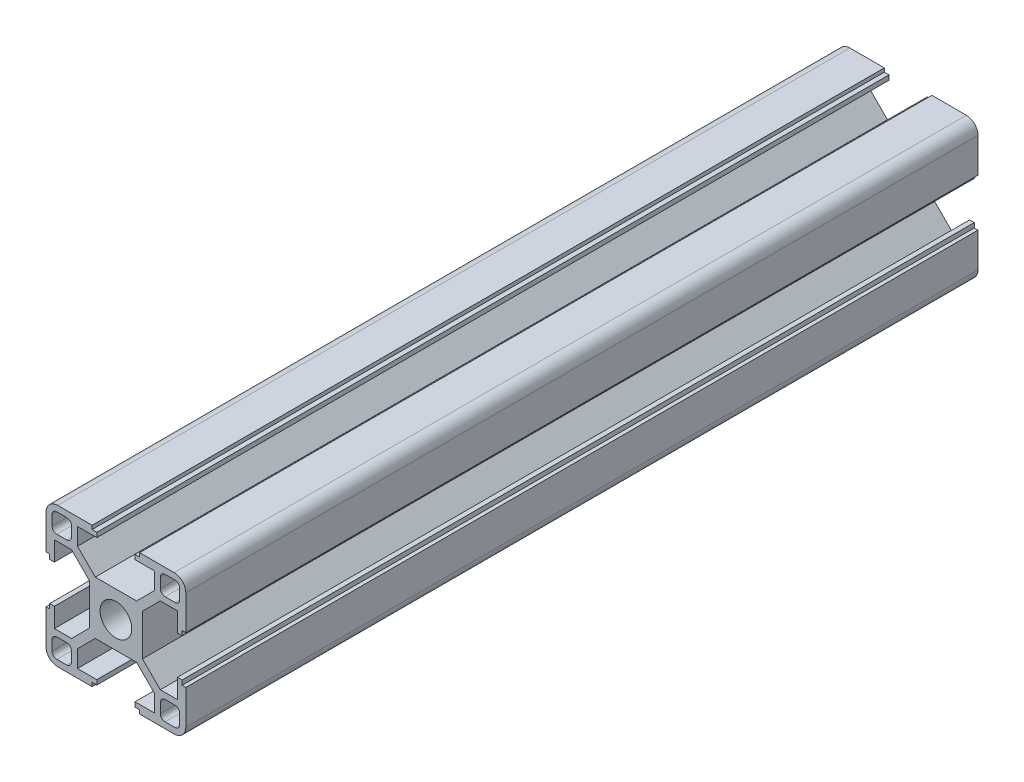
SolidWorks part; units mm, degrees
material "6061-T6 (SS)"
ref_plane "前视基准面" through (0, 0, 0) normal (0, 0, 1) x (1, 0, 0)
ref_plane "上视基准面" through (0, 0, 0) normal (0, 1, 0) x (1, 0, 0)
ref_plane "右视基准面" through (0, 0, 0) normal (1, 0, 0) x (0, 0, -1)
sketch "Sketch1" plane through (0, 0, 0) normal (0, 0, 1) x (1, 0, 0)
  line L0 (-5.1, 15) -> (-5.1, 14.2)
  line L1 (-12.5, -15) -> (12.5, -15)
  line L2 (-15, -12.5) -> (-15, 12.5)
  line L3 (-12.5, 15) -> (12.5, 15)
  line L4 (15, -12.5) -> (15, 12.5)
  line L5 (-15, -15) -> (15, 15) construction
  line L6 (-15, 15) -> (15, -15) construction
  line L7 (-5.1, 14.2) -> (-4.1, 14.2)
  line L8 (-4.1, 14.2) -> (-4.1, 13.2)
  line L9 (-4.1, 13.2) -> (-8.25, 13.2)
  line L10 (-8.25, 13.2) -> (-8.25, 9.5228)
  line L11 (-8.25, 9.5228) -> (-4.4272, 5.7)
  line L12 (-4.4272, 5.7) -> (4.4272, 5.7)
  line L13 (-5.1, 15) -> (5.1, 15)
  line L14 (0, 15) -> (0, 5.7) construction
  line L15 (8.25, 9.5228) -> (4.4272, 5.7)
  line L16 (8.25, 13.2) -> (8.25, 9.5228)
  line L17 (4.1, 13.2) -> (8.25, 13.2)
  line L18 (4.1, 14.2) -> (4.1, 13.2)
  line L19 (5.1, 14.2) -> (4.1, 14.2)
  line L20 (5.1, 15) -> (5.1, 14.2)
  line L21 (15, 5.1) -> (14.2, 5.1)
  line L22 (14.2, 5.1) -> (14.2, 4.1)
  line L23 (14.2, 4.1) -> (13.2, 4.1)
  line L24 (13.2, 4.1) -> (13.2, 8.25)
  line L25 (13.2, 8.25) -> (9.5228, 8.25)
  line L26 (9.5228, 8.25) -> (5.7, 4.4272)
  line L27 (5.7, 4.4272) -> (5.7, -4.4272)
  line L28 (15, 5.1) -> (15, -5.1)
  line L29 (9.5228, -8.25) -> (5.7, -4.4272)
  line L30 (13.2, -8.25) -> (9.5228, -8.25)
  line L31 (13.2, -4.1) -> (13.2, -8.25)
  line L32 (14.2, -4.1) -> (13.2, -4.1)
  line L33 (14.2, -5.1) -> (14.2, -4.1)
  line L34 (15, -5.1) -> (14.2, -5.1)
  line L35 (15, 0) -> (5.7, 0) construction
  line L36 (5.1, -15) -> (5.1, -14.2)
  line L37 (5.1, -14.2) -> (4.1, -14.2)
  line L38 (4.1, -14.2) -> (4.1, -13.2)
  line L39 (4.1, -13.2) -> (8.25, -13.2)
  line L40 (8.25, -13.2) -> (8.25, -9.5228)
  line L41 (8.25, -9.5228) -> (4.4272, -5.7)
  line L42 (4.4272, -5.7) -> (-4.4272, -5.7)
  line L43 (5.1, -15) -> (-5.1, -15)
  line L44 (-8.25, -9.5228) -> (-4.4272, -5.7)
  line L45 (-8.25, -13.2) -> (-8.25, -9.5228)
  line L46 (-4.1, -13.2) -> (-8.25, -13.2)
  line L47 (-4.1, -14.2) -> (-4.1, -13.2)
  line L48 (-5.1, -14.2) -> (-4.1, -14.2)
  line L49 (-5.1, -15) -> (-5.1, -14.2)
  line L50 (0, -15) -> (0, -5.7) construction
  line L51 (-15, -5.1) -> (-14.2, -5.1)
  line L52 (-14.2, -5.1) -> (-14.2, -4.1)
  line L53 (-14.2, -4.1) -> (-13.2, -4.1)
  line L54 (-13.2, -4.1) -> (-13.2, -8.25)
  line L55 (-13.2, -8.25) -> (-9.5228, -8.25)
  line L56 (-9.5228, -8.25) -> (-5.7, -4.4272)
  line L57 (-5.7, -4.4272) -> (-5.7, 4.4272)
  line L58 (-15, -5.1) -> (-15, 5.1)
  line L59 (-9.5228, 8.25) -> (-5.7, 4.4272)
  line L60 (-13.2, 8.25) -> (-9.5228, 8.25)
  line L61 (-13.2, 4.1) -> (-13.2, 8.25)
  line L62 (-14.2, 4.1) -> (-13.2, 4.1)
  line L63 (-14.2, 5.1) -> (-14.2, 4.1)
  line L64 (-15, 5.1) -> (-14.2, 5.1)
  line L65 (-15, 0) -> (-5.7, 0) construction
  line L66 (0, 0) -> (0, 5.7) construction
  circle A0 centre (0, 0) radius 3.4
  arc A1 (-12.5, -15) -> (-15, -12.5) centre (-12.5, -12.5) cw
  arc A2 (12.5, -15) -> (15, -12.5) centre (12.5, -12.5) ccw
  arc A3 (12.5, 15) -> (15, 12.5) centre (12.5, 12.5) cw
  arc A4 (-15, 12.5) -> (-12.5, 15) centre (-12.5, 12.5) cw
  point P0 (0, 0)
  dimension "D3" = 6.8
  dimension "D12" = 2.5
  dimension "D1" = 30
  dimension "D2" = 30
  dimension "D4" = 16.5
  dimension "D5" = 8.2
  dimension "D6" = 10.2
  dimension "D7" = 7.5
  dimension "D9" = 1.8
  dimension "D10" = 1.8
  dimension "D11" = 0.8
  dimension "D8" = 4
extrude "Extrude1" add sketch "Sketch1" along normal blind 170 contours A4 L2 L64 L63 L62 L61 L60 L59 L57 L56 L55 L54 L53 L52 L51 A1 L1 L49 L48 L47 L46 L45 L44 L42 L41 L40 L39 L38 L37 L36 A2 L4 L34 L33 L32 L31 L30 L29 L27 L26 L25 L24 L23 L22 L21 A3 L3 L20
sketch "Sketch2" plane through (0, 0, 170) normal (0, 0, 1) x (1, 0, 0)
  line L0 (13.7, 12.7) -> (13.7, 10.55)
  line L1 (-12.7, 13.7) -> (-10.55, 13.7)
  line L2 (-13.7, 12.7) -> (-13.7, 10.55)
  line L3 (-12.7, 9.55) -> (-10.55, 9.55)
  line L4 (-9.55, 12.7) -> (-9.55, 10.55)
  line L5 (-13.7, 13.7) -> (-9.55, 9.55) construction
  line L6 (-13.7, 9.55) -> (-9.55, 13.7) construction
  line L7 (12.7, 13.7) -> (10.55, 13.7)
  line L8 (9.55, 12.7) -> (9.55, 10.55)
  line L9 (12.7, 9.55) -> (10.55, 9.55)
  line L10 (12.7, -13.7) -> (10.55, -13.7)
  line L11 (13.7, -12.7) -> (13.7, -10.55)
  line L12 (12.7, -9.55) -> (10.55, -9.55)
  line L13 (9.55, -12.7) -> (9.55, -10.55)
  line L14 (-13.7, -12.7) -> (-13.7, -10.55)
  line L15 (-12.7, -13.7) -> (-10.55, -13.7)
  line L16 (-9.55, -12.7) -> (-9.55, -10.55)
  line L17 (-12.7, -9.55) -> (-10.55, -9.55)
  line L18 (0, 0) -> (-9.55, 9.55) construction
  line L19 (-12.5, 15) -> (-5.1, 15) construction
  line L20 (-15, 5.1) -> (-15, 12.5) construction
  line L21 (-13.2, 8.25) -> (-9.5228, 8.25) construction
  line L22 (-8.25, 13.2) -> (-8.25, 9.5228) construction
  arc A0 (-13.7, -12.7) -> (-12.7, -13.7) centre (-12.7, -12.7) ccw
  arc A1 (-10.55, -13.7) -> (-9.55, -12.7) centre (-10.55, -12.7) ccw
  arc A2 (-9.55, -10.55) -> (-10.55, -9.55) centre (-10.55, -10.55) ccw
  arc A3 (-13.7, -10.55) -> (-12.7, -9.55) centre (-12.7, -10.55) cw
  arc A4 (13.7, -10.55) -> (12.7, -9.55) centre (12.7, -10.55) ccw
  arc A5 (12.7, -13.7) -> (13.7, -12.7) centre (12.7, -12.7) ccw
  arc A6 (10.55, -13.7) -> (9.55, -12.7) centre (10.55, -12.7) cw
  arc A7 (10.55, -9.55) -> (9.55, -10.55) centre (10.55, -10.55) ccw
  arc A8 (13.7, 12.7) -> (12.7, 13.7) centre (12.7, 12.7) ccw
  arc A9 (13.7, 10.55) -> (12.7, 9.55) centre (12.7, 10.55) cw
  arc A10 (9.55, 10.55) -> (10.55, 9.55) centre (10.55, 10.55) ccw
  arc A11 (10.55, 13.7) -> (9.55, 12.7) centre (10.55, 12.7) ccw
  arc A12 (-10.55, 13.7) -> (-9.55, 12.7) centre (-10.55, 12.7) cw
  arc A13 (-10.55, 9.55) -> (-9.55, 10.55) centre (-10.55, 10.55) ccw
  arc A14 (-13.7, 10.55) -> (-12.7, 9.55) centre (-12.7, 10.55) ccw
  arc A15 (-12.7, 13.7) -> (-13.7, 12.7) centre (-12.7, 12.7) ccw
  point P0 (-11.625, 11.625)
  dimension "D2" = 1
  dimension "D3" = 1.3
  dimension "D4" = 1.3
  dimension "D5" = 1.3
  dimension "D6" = 1.3
  dimension "D1" = 4
extrude "Extrude2" cut sketch "Sketch2" against normal through all
